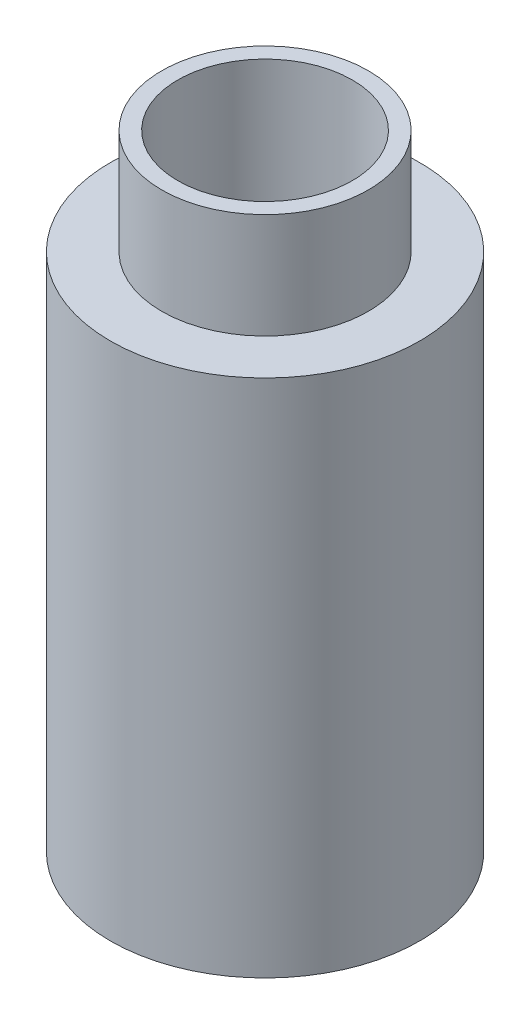
SolidWorks part; units mm, degrees
ref_plane "Front Plane" through (0, 0, 0) normal (0, 0, 1) x (1, 0, 0)
ref_plane "Top Plane" through (0, 0, 0) normal (0, 1, 0) x (1, 0, 0)
ref_plane "Right Plane" through (0, 0, 0) normal (1, 0, 0) x (0, 0, -1)
sketch "Sketch1" plane through (0, 0, 0) normal (0, 1, 0) x (1, 0, 0)
  circle A0 centre (0, 0) radius 9.4488
  dimension "D1" = 18.8976
extrude "Boss-Extrude1" add sketch "Sketch1" along normal blind 31.75
sketch "Sketch2" plane through (0, 31.75, 0) normal (0, 1, 0) x (1, 0, 0)
  circle A0 centre (0, 0) radius 6.3119
  dimension "D1" = 12.6238
extrude "Boss-Extrude2" add sketch "Sketch2" along normal blind 6.4262
sketch "Sketch3" plane through (0, 38.1762, 0) normal (0, 1, 0) x (1, 0, 0)
  circle A0 centre (0, 0) radius 5.334
  dimension "D1" = 10.668
extrude "Cut-Extrude1" cut sketch "Sketch3" against normal through all
